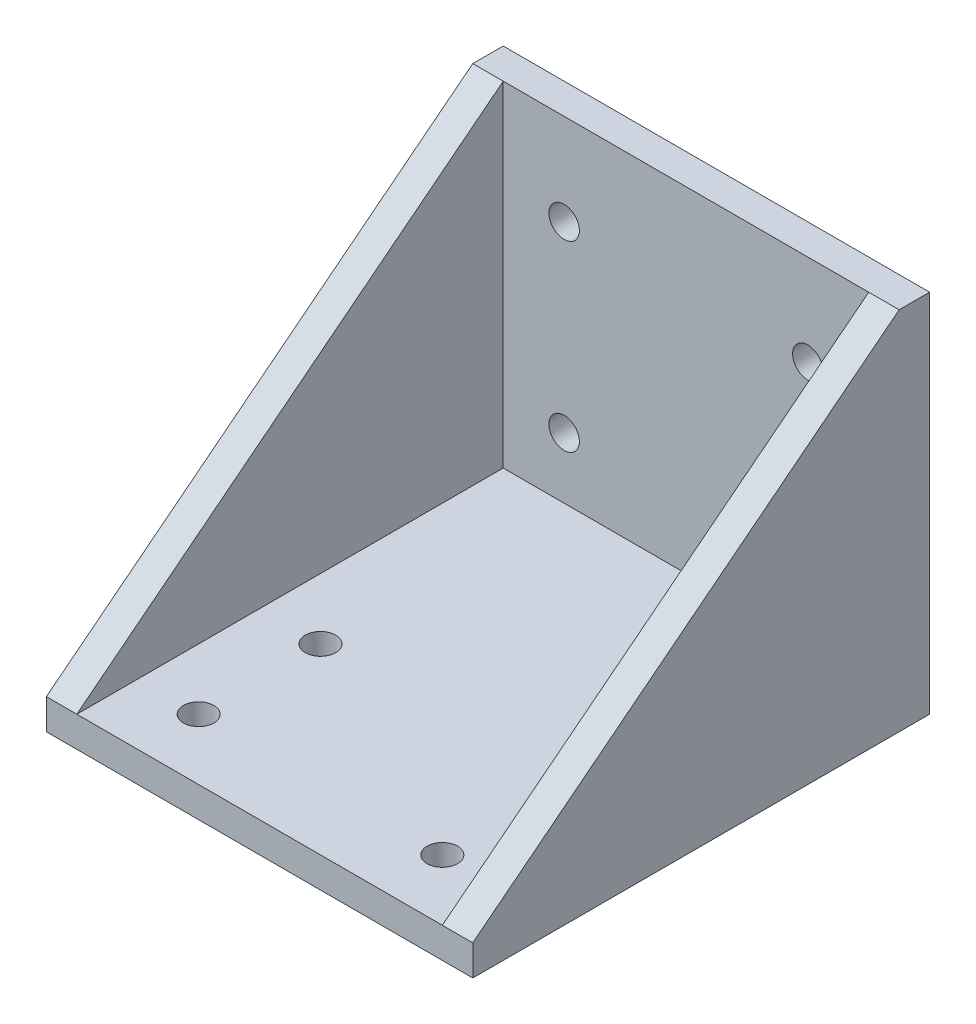
SolidWorks part; units mm, degrees
ref_plane "前视基准面" through (0, 0, 0) normal (0, 0, 1) x (1, 0, 0)
ref_plane "上视基准面" through (0, 0, 0) normal (0, 1, 0) x (1, 0, 0)
ref_plane "右视基准面" through (0, 0, 0) normal (1, 0, 0) x (0, 0, -1)
sketch "草图1" plane through (0, 0, 0) normal (0, 0, 1) x (1, 0, 0)
  line L1 (-35, -30) -> (35, -30)
  line L2 (-35, -30) -> (-35, 30)
  line L3 (-35, 30) -> (35, 30)
  line L4 (35, -30) -> (35, 30)
  line L5 (-35, -30) -> (35, 30) construction
  line L6 (-35, 30) -> (35, -30) construction
  circle A0 centre (-20, 15) radius 2.5
  circle A1 centre (20, 15) radius 2.5
  circle A2 centre (-20, -15) radius 2.5
  circle A3 centre (20, -15) radius 2.5
  point P0 (0, 0)
  dimension "D3" = 5
  dimension "D4" = 5
  dimension "D5" = 5
  dimension "D6" = 5
  dimension "D1" = 70
  dimension "D2" = 60
  dimension "D7" = 15
  dimension "D8" = 15
  dimension "D9" = 15
  dimension "D10" = 15
  dimension "D11" = 15
  dimension "D12" = 15
  dimension "D13" = 15
  dimension "D14" = 15
extrude "凸台-拉伸1" add sketch "草图1" along normal blind 5
sketch "草图2" plane through (0, 0, 5) normal (0, 0, 1) x (1, 0, 0)
  line L1 (-35, 30) -> (35, 30)
  line L2 (-35, 30) -> (-35, -30)
  line L3 (-35, -30) -> (35, -30)
  line L4 (35, 30) -> (35, -30)
  line L5 (-30, 30) -> (30, 30)
  line L6 (-30, 30) -> (-30, -25)
  line L7 (-30, -25) -> (30, -25)
  line L8 (30, 30) -> (30, -25)
  line M7 (35, -30) -> (35, 30)
  line M8 (35, 30) -> (-35, 30)
  line M9 (-35, 30) -> (-35, -30)
  line M10 (-35, -30) -> (35, -30)
  dimension "D1" = 5
  dimension "D2" = 5
  dimension "D3" = 5
extrude "凸台-拉伸2" add sketch "草图2" along normal blind 70 contours L8 L7 L6 M8 M9 M10 M7
sketch "草图3" plane through (-35, 0, 0) normal (-1, 0, 0) x (0, 0, 1)
  line L0 (5, 30) -> (75, -25)
  line L1 (75, 30) -> (0, 30) construction
  line L2 (75, 30) -> (75, -30) construction
  line L3 (75, -25) -> (75, 30)
  line L4 (75, 30) -> (5, 30)
  line L5 (0, 30) -> (0, -30) construction
  line L6 (75, -30) -> (0, -30) construction
  dimension "D1" = 5
  dimension "D2" = 5
extrude "切除-拉伸1" cut sketch "草图3" against normal blind 70
sketch "草图4" plane through (0, -30, 0) normal (0, -1, 0) x (1, 0, 0)
  line L0 (-35, 75) -> (35, 75) construction
  line L1 (-35, 75) -> (-35, 0) construction
  line L2 (35, 75) -> (35, 0) construction
  circle A0 centre (-20, 65) radius 2.5
  circle A1 centre (20, 65) radius 2.5
  circle A2 centre (-20, 45) radius 2.5
  circle A3 centre (20, 45) radius 2.5
  dimension "D1" = 5
  dimension "D2" = 5
  dimension "D3" = 5
  dimension "D4" = 5
  dimension "D5" = 40
  dimension "D6" = 20
  dimension "D7" = 10
  dimension "D8" = 15
  dimension "D9" = 20
  dimension "D10" = 15
  dimension "D11" = 15
  dimension "D12" = 10
extrude "切除-拉伸2" cut sketch "草图4" against normal blind 5
